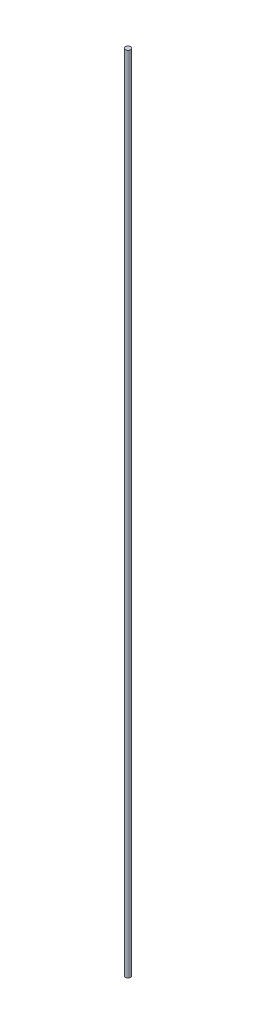
SolidWorks part; units mm, degrees
ref_plane "Спереди" through (0, 0, 0) normal (0, 0, 1) x (1, 0, 0)
ref_plane "Сверху" through (0, 0, 0) normal (0, 1, 0) x (1, 0, 0)
ref_plane "Справа" through (0, 0, 0) normal (1, 0, 0) x (0, 0, -1)
sketch "Эскиз2" plane through (0, 0, 0) normal (0, 0, 1) x (1, 0, 0)
  line L5 (-2.5, 380) -> (0, 380)
  line L6 (-2.5, 380) -> (-2.5, -380)
  line L7 (-2.5, -380) -> (0, -380)
  line L8 (0, 380) -> (0, -380)
  line L9 (-2.5, 380) -> (0, -380) construction
  line L10 (-2.5, -380) -> (0, 380) construction
  point P0 (-1.25, 0)
  point P5 (0, 0)
  dimension "D1" = 2.5
  dimension "D2" = 760
revolve "Повернуть1" add sketch "Эскиз2" angle 360 about L6
equation "\"Ширина груза\"= 420"
equation "\"Глубина груза\"= 490"
equation "\"Высота груза\"= 297"
equation "\"Ширина ячейки\"= \"Ширина груза\" + 10"
equation "\"Глубина ячейки\"= \"Глубина груза\" + 10"
equation "\"Высота ячейки\"= \"Высота груза\" + 10 + 13"
equation "\"Колво ячеек ширина\"= 2"
equation "\"Колво ячеек высота\"= 2"
equation "\"Толщина стенки\"= 10"
equation "\"Крепление дверцы\"= 5"
equation "\"Ширина рейки\"= \"Толщина шестерни\""
equation "\"Высота рейки\"= 20"
equation "\"Высота пола\"= 20"
equation "\"Колво полозьев\"= 5"
equation "\"Отступ рейки\"= 20"
equation "\"Глубина каретки\"= \"Глубина ячейки\" + 80"
equation "\"Длинна рейки\"= ( \"Ширина ячейки\" + \"Толщина стенки\" + \"Крепление дверцы\" ) * \"Колво ячеек ширина\" + \"Ширина ячейки выгрузки\" * \"Колво выгрузки\" + \"Толщина стенки\""
equation "\"Отступ шпильки\"= 20"
equation "\"Диаметр шпильки\"= 5"
equation "\"Длинна шпильки\"= ( \"Высота ячейки\" + \"Толщина стенки\" + \"Высота пола\" ) * \"Колво ячеек высота\" + ( \"Толщина стенки\" + \"Отступ рейки\" ) * 2"
equation "\"D1@Эскиз2\"= \"Диаметр шпильки\" / 2"
equation "\"D2@Эскиз2\"= \"Длинна шпильки\""
equation "\"Ширина пластины\"= 50  "
equation "\"Высота зона выгрузки\"= \"Высота ячейки\" * 2 + \"Толщина стенки\" * 2"
equation "\"Колво выгрузки\"= 1"
equation "\"Отступ крепления мотора фиксации\" = 30"
equation "\"Мотор X ширина корпуса\"= 42.3"
equation "\"Мотор X высота корпуса\"= 42.3"
equation "\"Мотор X длина корпуса\"= 40"
equation "\"Мотор X вылет вала\"= 19.8"
equation "\"Мотор Y ширина корпуса\"= 42.3"
equation "\"Мотор Y высота корпуса\"= 42.3"
equation "\"Мотор Y длина корпуса\"= 48"
equation "\"Мотор Y вылет вала\"= 30"
equation "\"Мотор Z ширина корпуса\"= 42"
equation "\"Мотор Z высота корпуса\"= 42"
equation "\"Мотор Z длина корпуса\"= 40"
equation "\"Мотор Z вылет вала\"= 23"
equation "\"Мотор диаметр вала ПРЕДВ\"= 5"
equation "\"Мотор шаг крепления ПРЕДВ\"= 31"
equation "\"Мотор диаметр отверстий ПРЕДВ\"= 3"
equation "\"Мотор глубина отверстий ПРЕДВ\"= 4.5"
equation "\"Мотор диаметр буртика ПРЕДВ\"= 22"
equation "\"Мотор высота буртика ПРЕДВ\"= 2"
equation "\"Мотор диаметр шкива ПРЕДВ\"= 16"
equation "\"Мотор длина шкива ПРЕДВ\"= 12"
equation "\"Мотор отступ шкива ПРЕДВ\"= 5"
equation "\"Мотор X шаг градусов\"= 1.8"
equation "\"Мотор X ток А\"= 1.5"
equation "\"Мотор X сопротивление Ом\"= 1.3"
equation "\"Мотор X индуктивность мГн\"= 2"
equation "\"Мотор Y шаг градусов\"= 1.8"
equation "\"Мотор Y ток А\"= 2.2"
equation "\"Мотор Y сопротивление Ом\"= 0.9"
equation "\"Мотор Y индуктивность мГн\"= 2"
equation "\"Мотор Z шаг градусов\"= 1.8"
equation "\"Мотор Z ток А\"= 1"
equation "\"Мотор Z сопротивление Ом\"= 4"
equation "\"Мотор Z индуктивность мГн\"= 8"
equation "\"Мотор Y диаметр ротора\"= 25.78"
equation "\"Ширина ячейки выгрузки\"= \"Ширина ячейки\" + \"Толщина стенки\" + \"Отступ крепления мотора фиксации\"*2"
